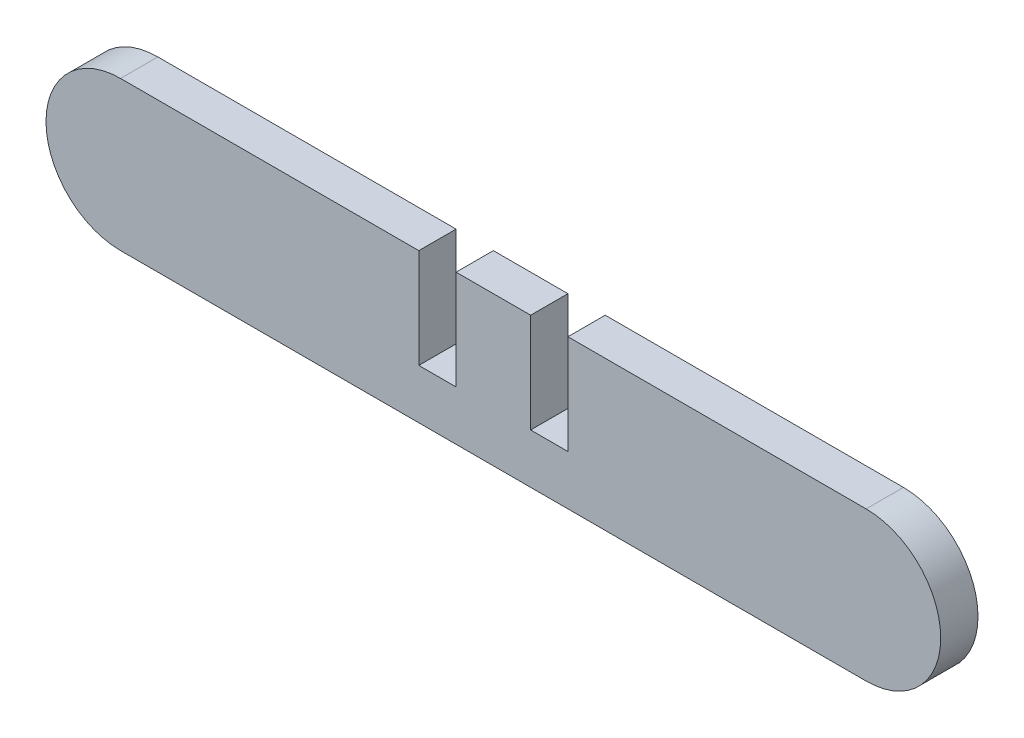
SolidWorks part; units mm, degrees
ref_plane "前视基准面" through (0, 0, 0) normal (0, 0, 1) x (1, 0, 0)
ref_plane "上视基准面" through (0, 0, 0) normal (0, 1, 0) x (1, 0, 0)
ref_plane "右视基准面" through (0, 0, 0) normal (1, 0, 0) x (0, 0, -1)
sketch "草图1" plane through (0, 0, 0) normal (0, 0, 1) x (1, 0, 0)
  line L0 (30, 0) -> (-30, 0) construction
  line L2 (30, -6) -> (-30, -6)
  line L3 (30, 6) -> (-30, 6)
  arc A0 (30, -6) -> (30, 6) centre (30, 0) ccw
  arc A1 (-30, 6) -> (-30, -6) centre (-30, 0) ccw
  point P5 (0, 0)
  dimension "D2" = 6
  dimension "D1" = 60
extrude "凸台-拉伸1" add sketch "草图1" along normal blind 3
sketch "草图2" plane through (0, 0, 3) normal (0, 0, 1) x (1, 0, 0)
  line L0 (0, 1.4054) -> (0, 0) construction
  line L1 (-3, 6) -> (-6, 6)
  line L2 (-3, 6) -> (-3, -2)
  line L3 (-3, -2) -> (-6, -2)
  line L4 (-6, 6) -> (-6, -2)
  line L5 (-4.5, -2) -> (-4.5, 6) construction
  line L6 (-3, 2) -> (-6, 2) construction
  line L7 (3, 2) -> (6, 2) construction
  line L8 (30, 6) -> (-30, 6) construction
  line L9 (4.5, -2) -> (4.5, 6) construction
  line L10 (6, 6) -> (6, -2)
  line L11 (3, -2) -> (6, -2)
  line L12 (3, 6) -> (3, -2)
  line L13 (3, 6) -> (6, 6)
  dimension "D1" = 8
  dimension "D2" = 3
  dimension "D3" = 4.5
extrude "切除-拉伸1" cut sketch "草图2" against normal blind 4
